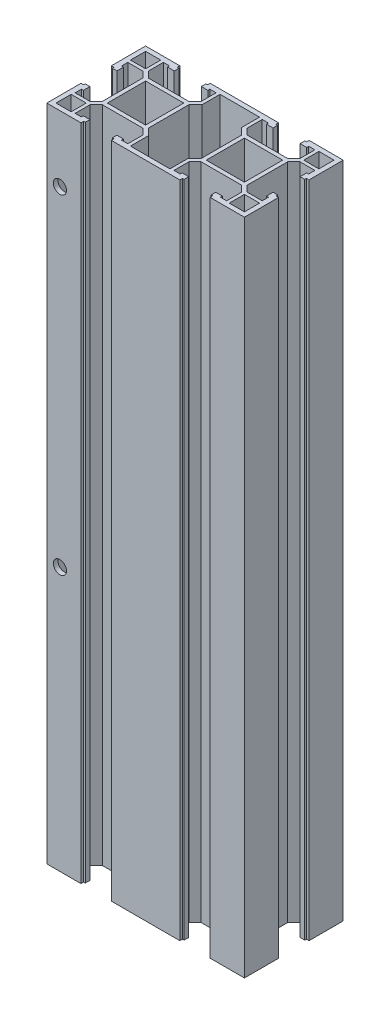
SolidWorks part; units mm, degrees
material "Простая углеродистая сталь"
ref_plane "Спереди" through (0, 0, 0) normal (0, 0, 1) x (1, 0, 0)
ref_plane "Сверху" through (0, 0, 0) normal (0, 1, 0) x (1, 0, 0)
ref_plane "Справа" through (0, 0, 0) normal (1, 0, 0) x (0, 0, -1)
sketch "Эскиз1" plane through (0, 0, 0) normal (0, 1, 0) x (1, 0, 0)
  line L0 (-258.3419, 0) -> (12658.7539, 0) construction
  line L1 (0, -258.3419) -> (0, 12658.7539) construction
  line L2 (15, -258.3419) -> (15, 12658.7539) construction
  line L3 (-15, -258.3419) -> (-15, 12658.7539) construction
  line L4 (22, 7) -> (8, 7)
  line L5 (-30, -15) -> (30, -15)
  line L6 (-30, -15) -> (-30, 15)
  line L7 (-30, 15) -> (30, 15)
  line L8 (30, -15) -> (30, 15)
  line L9 (-30, -15) -> (30, 15) construction
  line L10 (-30, 15) -> (30, -15) construction
  line L11 (-22, -7) -> (-8, -7)
  line L12 (-22, -7) -> (-22, 7)
  line L13 (-22, 7) -> (-8, 7)
  line L14 (-8, -7) -> (-8, 7)
  line L15 (-22, -7) -> (-8, 7) construction
  line L16 (-22, 7) -> (-8, -7) construction
  line L17 (8, -7) -> (8, 7)
  line L18 (22, -7) -> (8, -7)
  line L19 (22, -7) -> (22, 7)
  line L20 (-22, -7) -> (-30, -15) construction
  line L21 (-22, 7) -> (-30, 15) construction
  line L22 (22, 7) -> (30, 15) construction
  line L23 (22, -7) -> (30, -15) construction
  line L24 (24, 9) -> (28.6, 9)
  line L25 (-24, 13.6) -> (-28.6, 13.6)
  line L26 (-24, 13.6) -> (-24, 9)
  line L27 (-24, 9) -> (-28.6, 9)
  line L28 (-28.6, 13.6) -> (-28.6, 9)
  line L29 (-24, 13.6) -> (-28.6, 9) construction
  line L30 (-24, 9) -> (-28.6, 13.6) construction
  line L31 (28.6, 13.6) -> (28.6, 9)
  line L32 (24, 13.6) -> (28.6, 13.6)
  line L33 (24, 13.6) -> (24, 9)
  line L34 (-24, -9) -> (-28.6, -9)
  line L35 (-28.6, -13.6) -> (-28.6, -9)
  line L36 (-24, -13.6) -> (-28.6, -13.6)
  line L37 (-24, -13.6) -> (-24, -9)
  line L38 (24, -13.6) -> (24, -9)
  line L39 (24, -13.6) -> (28.6, -13.6)
  line L40 (28.6, -13.6) -> (28.6, -9)
  line L41 (24, -9) -> (28.6, -9)
  line L42 (-28.4, 8) -> (-23.8485, 8)
  line L43 (-23.8485, 8) -> (-22, 6.1515)
  line L44 (-28.4, 8) -> (-28.4, 6.1)
  line L45 (-28.4, 6.1) -> (-27.8, 6.1)
  line L46 (-27.8, 6.1) -> (-27.8, 4.1)
  line L47 (-27.8, 4.1) -> (-29.2, 4.1)
  line L48 (-29.2, 4.1) -> (-29.2, 4.6)
  line L49 (-29.2, -4.1) -> (-29.2, -4.6)
  line L50 (-30, 4.6) -> (-29.2, 4.6)
  line L51 (-30, -4.6) -> (-29.2, -4.6)
  line L52 (-27.8, -4.1) -> (-29.2, -4.1)
  line L53 (-28.4, -6.1) -> (-27.8, -6.1)
  line L54 (-27.8, -6.1) -> (-27.8, -4.1)
  line L55 (-28.4, -8) -> (-28.4, -6.1)
  line L56 (-28.4, -8) -> (-23.8485, -8)
  line L57 (-23.8485, -8) -> (-22, -6.1515)
  line L58 (-19.6, 15) -> (-19.6, 14.2)
  line L59 (-19.1, 14.2) -> (-19.6, 14.2)
  line L60 (-19.1, 12.8) -> (-19.1, 14.2)
  line L61 (-21.1, 12.8) -> (-19.1, 12.8)
  line L62 (-21.1, 13.4) -> (-21.1, 12.8)
  line L63 (-23, 13.4) -> (-21.1, 13.4)
  line L64 (-23, 13.4) -> (-23, 8.8485)
  line L65 (-23, 8.8485) -> (-21.1515, 7)
  line L66 (-10.4, 15) -> (-10.4, 14.2)
  line L67 (-10.9, 14.2) -> (-10.4, 14.2)
  line L68 (-10.9, 12.8) -> (-10.9, 14.2)
  line L69 (-8.9, 12.8) -> (-10.9, 12.8)
  line L70 (-8.9, 13.4) -> (-8.9, 12.8)
  line L71 (-7, 13.4) -> (-8.9, 13.4)
  line L72 (-6, 13.6) -> (-6, 8.1515)
  line L73 (-7, 13.4) -> (-7, 8.8485)
  line L74 (-7, 8.8485) -> (-8.8485, 7)
  line L75 (-6, 13.6) -> (6, 13.6)
  line L76 (-6, 8.1515) -> (-8, 6.1515)
  line L77 (-10.9, 12.8) -> (-10.9, 14.2)
  line L78 (-10.9, 14.2) -> (-10.4, 14.2)
  line L79 (-10.4, 15) -> (-10.4, 14.2)
  line L80 (-8.9, 13.4) -> (-8.9, 12.8)
  line L81 (-8.9, 12.8) -> (-10.9, 12.8)
  line L82 (-7, 8.8485) -> (-8.8485, 7)
  line L83 (-7, 13.4) -> (-7, 8.8485)
  line L84 (-7, 13.4) -> (-8.9, 13.4)
  line L85 (-21.1, 13.4) -> (-21.1, 12.8)
  line L86 (-21.1, 12.8) -> (-19.1, 12.8)
  line L87 (-19.1, 14.2) -> (-19.6, 14.2)
  line L88 (-19.1, 12.8) -> (-19.1, 14.2)
  line L89 (-19.6, 15) -> (-19.6, 14.2)
  line L90 (-23, 13.4) -> (-21.1, 13.4)
  line L91 (-23, 13.4) -> (-23, 8.8485)
  line L92 (-23, 8.8485) -> (-21.1515, 7)
  line L93 (-24, 8.1515) -> (-22, 6.1515)
  line L94 (-24, 13.6) -> (-24, 8.1515)
  line L95 (-24, 13.6) -> (-30, 13.6)
  line L96 (-19.1, -14.2) -> (-19.6, -14.2)
  line L97 (-19.6, -15) -> (-19.6, -14.2)
  line L98 (-19.1, -12.8) -> (-19.1, -14.2)
  line L99 (-21.1, -12.8) -> (-19.1, -12.8)
  line L100 (-21.1, -13.4) -> (-21.1, -12.8)
  line L101 (-23, -13.4) -> (-21.1, -13.4)
  line L102 (-23, -13.4) -> (-23, -8.8485)
  line L103 (-23, -8.8485) -> (-21.1515, -7)
  line L104 (-6, -8.1515) -> (-8, -6.1515)
  line L105 (-7, -8.8485) -> (-8.8485, -7)
  line L106 (-10.4, -15) -> (-10.4, -14.2)
  line L107 (-10.9, -14.2) -> (-10.4, -14.2)
  line L108 (-10.9, -12.8) -> (-10.9, -14.2)
  line L109 (-8.9, -13.4) -> (-8.9, -12.8)
  line L110 (-8.9, -12.8) -> (-10.9, -12.8)
  line L111 (-7, -13.4) -> (-8.9, -13.4)
  line L112 (-7, -13.4) -> (-7, -8.8485)
  line L113 (-6, -13.6) -> (-6, -8.1515)
  line L114 (-6, -13.6) -> (6, -13.6)
  line L115 (10.9, 12.8) -> (10.9, 14.2)
  line L116 (-20.8, -5.8) -> (-9.2, -5.8)
  line L117 (-20.8, -5.8) -> (-20.8, 5.8)
  line L118 (-20.8, 5.8) -> (-9.2, 5.8)
  line L119 (-9.2, -5.8) -> (-9.2, 5.8)
  line L120 (-20.8, -5.8) -> (-9.2, 5.8) construction
  line L121 (-20.8, 5.8) -> (-9.2, -5.8) construction
  line L122 (10.9, 14.2) -> (10.4, 14.2)
  line L123 (10.4, 15) -> (10.4, 14.2)
  line L124 (7, 13.4) -> (8.9, 13.4)
  line L125 (8.9, 13.4) -> (8.9, 12.8)
  line L126 (8.9, 12.8) -> (10.9, 12.8)
  line L127 (6, 8.1515) -> (8, 6.1515)
  line L128 (7, 8.8485) -> (8.8485, 7)
  line L129 (7, 13.4) -> (7, 8.8485)
  line L130 (6, 13.6) -> (6, 8.1515)
  line L131 (19.6, 15) -> (19.6, 14.2)
  line L132 (19.1, 14.2) -> (19.6, 14.2)
  line L133 (19.1, 12.8) -> (19.1, 14.2)
  line L134 (21.1, 13.4) -> (21.1, 12.8)
  line L135 (21.1, 12.8) -> (19.1, 12.8)
  line L136 (23, 13.4) -> (21.1, 13.4)
  line L137 (23, 13.4) -> (23, 8.8485)
  line L138 (23, 8.8485) -> (21.1515, 7)
  line L139 (23.8485, 8) -> (22, 6.1515)
  line L140 (28.4, 8) -> (23.8485, 8)
  line L141 (28.4, 8) -> (28.4, 6.1)
  line L142 (28.4, 6.1) -> (27.8, 6.1)
  line L143 (27.8, 6.1) -> (27.8, 4.1)
  line L144 (29.2, 4.1) -> (29.2, 4.6)
  line L145 (27.8, 4.1) -> (29.2, 4.1)
  line L146 (30, 4.6) -> (29.2, 4.6)
  line L147 (23, -8.8485) -> (21.1515, -7)
  line L148 (23.8485, -8) -> (22, -6.1515)
  line L149 (28.4, -8) -> (23.8485, -8)
  line L150 (28.4, -8) -> (28.4, -6.1)
  line L151 (28.4, -6.1) -> (27.8, -6.1)
  line L152 (30, -4.6) -> (29.2, -4.6)
  line L153 (27.8, -6.1) -> (27.8, -4.1)
  line L154 (27.8, -4.1) -> (29.2, -4.1)
  line L155 (29.2, -4.1) -> (29.2, -4.6)
  line L156 (20.8, 5.8) -> (9.2, 5.8)
  line L157 (9.2, -5.8) -> (9.2, 5.8)
  line L158 (20.8, -5.8) -> (9.2, -5.8)
  line L159 (20.8, -5.8) -> (20.8, 5.8)
  line L160 (19.6, -15) -> (19.6, -14.2)
  line L161 (19.1, -14.2) -> (19.6, -14.2)
  line L162 (19.1, -12.8) -> (19.1, -14.2)
  line L163 (21.1, -13.4) -> (21.1, -12.8)
  line L164 (21.1, -12.8) -> (19.1, -12.8)
  line L165 (23, -13.4) -> (23, -8.8485)
  line L166 (23, -13.4) -> (21.1, -13.4)
  line L167 (10.4, -15) -> (10.4, -14.2)
  line L168 (10.9, -14.2) -> (10.4, -14.2)
  line L169 (10.9, -12.8) -> (10.9, -14.2)
  line L170 (8.9, -12.8) -> (10.9, -12.8)
  line L171 (8.9, -13.4) -> (8.9, -12.8)
  line L172 (7, -13.4) -> (8.9, -13.4)
  line L173 (6, -13.6) -> (6, -8.1515)
  line L174 (7, -13.4) -> (7, -8.8485)
  line L175 (7, -8.8485) -> (8.8485, -7)
  line L176 (6, -8.1515) -> (8, -6.1515)
  point P9 (0, 0)
  point P14 (-15, 0)
  point P23 (-26.3, 11.3)
  point P105 (-15, 0)
  point P121 (0, 13.6)
  point P169 (0, -13.6)
  dimension "D1" = 15
  dimension "D2" = 60
  dimension "D3" = 30
  dimension "D4" = 8
  dimension "D5" = 8
  dimension "D6" = 1.4
  dimension "D7" = 4.6
  dimension "D8" = 4.1
  dimension "D9" = 4.6
  dimension "D10" = 2.2
  dimension "D11" = 1.6
  dimension "D12" = 0.6
  dimension "D13" = 0.8
  dimension "D14" = 2
  dimension "D15" = 1.2
extrude "Бобышка-Вытянуть2" add sketch "Эскиз1" along normal blind 200 contours L176 L173 L114 L113 L104 L14 L11 L105 L112 L111 L109 L110 L108 L107 L106 L5 L167 L168 L169 L170 L171 L172 L174 L175 L18 L17 | L11 L14 L13 L12 L119 L116 L117 L118 | L102 L103 L11 L12 L57 L56 L55 L53 L54 L52 L49 L51 L6 L5 L97 L96 L98 L99 L100 L101 L37 L36 L35 L34 | L18 L19 L4 L17 L159 L158 L157 L156 | L165 L166 L163 L164 L162 L161 L160 L5 L8 L152 L155 L154 L153 L151 L150 L149 L148 L19 L18 L147 L38 L41 L40 L39 | L146 L8 L7 L131 L132 L133 L135 L134 L136 L137 L138 L4 L19 L139 L140 L141 L142 L143 L145 L144 L33 L32 L31 L24 | L75 L130 L127 L17 L4 L128 L129 L124 L125 L126 L115 L122 L123 L7 L66 L67 L68 L69 L70 L71 L73 L74 L13 L14 L76 L72 | L95 L25 L26 L94 L93 L43 L12 L13 L65 L64 L63 L62 L61 L60 L59 L58 L7 L6 | L28 L95 L6 L50 L48 L47 L46 L45 L44 L42 L93 L94 L27
sketch "Эскиз2" plane through (0, 0, 0) normal (0, 0, 1) x (1, 0, 0)
  line L0 (-23.8485, 0) -> (-22, 0) construction
  line L1 (-22, 0) -> (-22, 200) construction
  line L2 (-22, 200) -> (-23.8485, 200) construction
  line L3 (-28.4, 0) -> (-23.8485, 0) construction
  line L4 (-23.8485, 200) -> (-28.4, 200) construction
  line L5 (-28.4, 200) -> (-28.4, 0) construction
  line L6 (-23.8485, 0) -> (-22, 0)
  line L7 (-22, 0) -> (-22, 200)
  line L8 (-22, 200) -> (-23.8485, 200)
  line L9 (-28.4, 0) -> (-23.8485, 0)
  line L10 (-23.8485, 200) -> (-28.4, 200)
  line L11 (-28.4, 200) -> (-28.4, 0)
  line L12 (-30, 200) -> (-30, 0) construction
  line L13 (-26, -620) -> (-26, 49380) construction
  circle A0 centre (-26, 180) radius 2
  circle A2 centre (-26, 80) radius 2
  dimension "D1" = 4
  dimension "D4" = 100
  dimension "D2" = 4
  dimension "D3" = 20
extrude "Вырез-Вытянуть1" cut sketch "Эскиз2" against normal through all both and the other way through all contours A2 | A0
